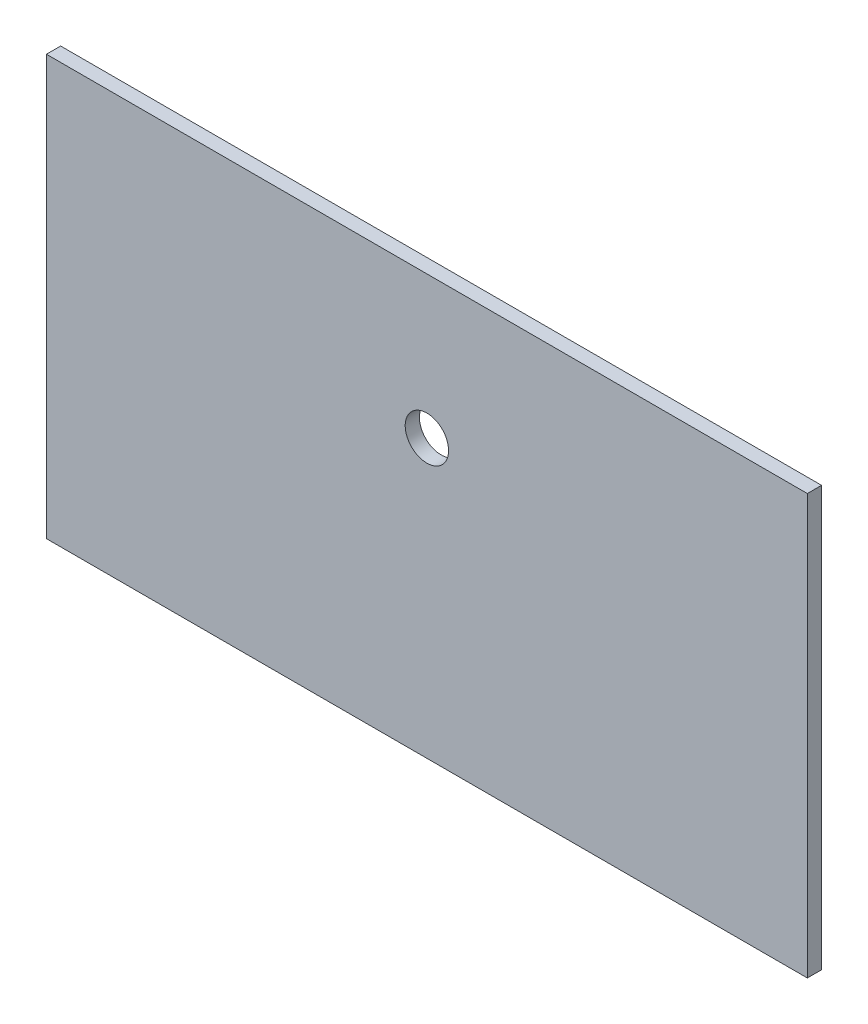
SolidWorks part; units mm, degrees
ref_plane "Plano frontal" through (0, 0, 0) normal (0, 0, 1) x (1, 0, 0)
ref_plane "Plano superior" through (0, 0, 0) normal (0, 1, 0) x (1, 0, 0)
ref_plane "Plano direito" through (0, 0, 0) normal (1, 0, 0) x (0, 0, -1)
sketch "Esboço1" plane through (0, 0, 0) normal (0, 0, 1) x (1, 0, 0)
  line L0 (53.5, 59) -> (53.5, 0) construction
  line L1 (0, 0) -> (107, 0)
  line L2 (0, 0) -> (0, 59)
  line L3 (0, 59) -> (107, 59)
  line L4 (107, 0) -> (107, 59)
  circle A0 centre (53.5, 39) radius 3.05
  dimension "D3" = 6.1
  dimension "D1" = 59
  dimension "D2" = 107
  dimension "D4" = 20
extrude "Ressalto-extrusão1" add sketch "Esboço1" along normal blind 2
